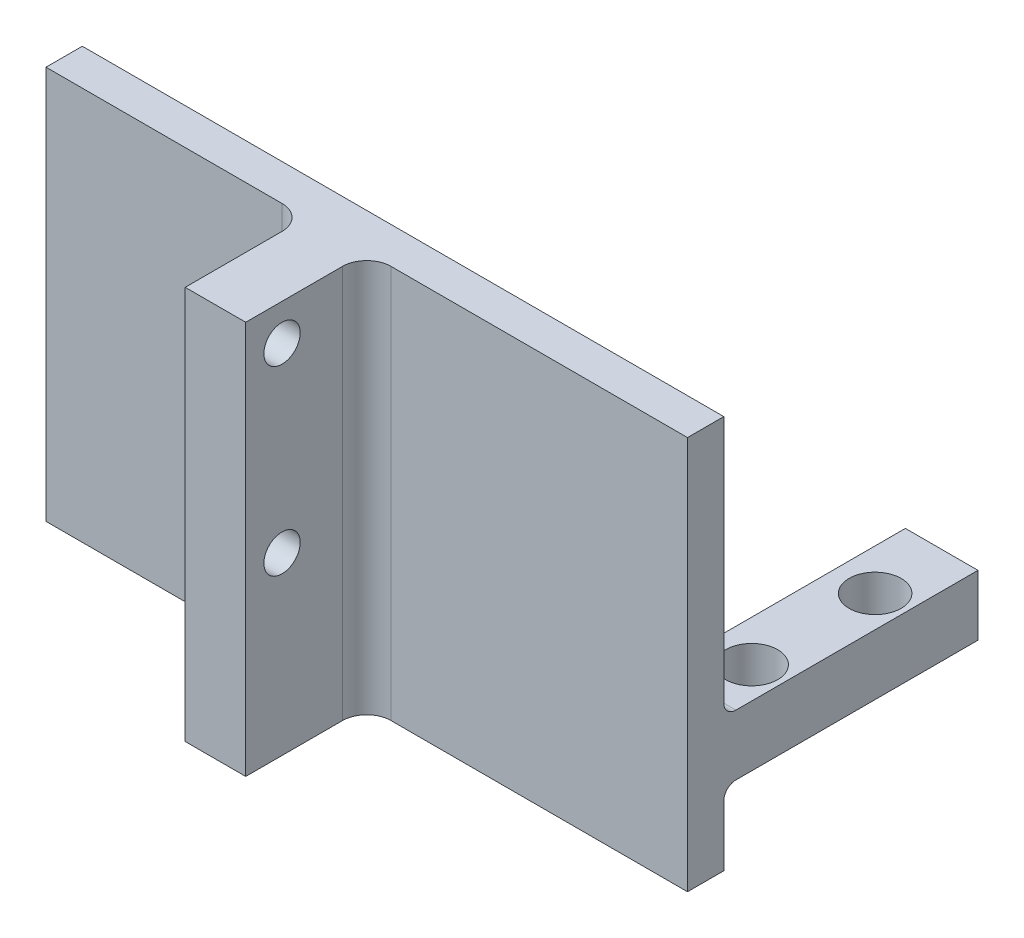
SolidWorks part; units mm, degrees
ref_plane "Front Plane" through (0, 0, 0) normal (0, 0, 1) x (1, 0, 0)
ref_plane "Top Plane" through (0, 0, 0) normal (0, 1, 0) x (1, 0, 0)
ref_plane "Right Plane" through (0, 0, 0) normal (1, 0, 0) x (0, 0, -1)
sketch "Sketch1" plane through (0, 0, 0) normal (0, 0, 1) x (1, 0, 0)
  line L0 (26.5, -7.5) -> (26.5, -5) construction
  line L1 (-26.5, 21.5) -> (26.5, 21.5)
  line L3 (-26.5, -11) -> (26.5, -11)
  line L4 (26.5, 21.5) -> (26.5, -11)
  line L8 (-26.5, 21.5) -> (-26.5, -11)
  line L9 (18, -11) -> (-18, -11) construction
  line L10 (-15.75, 21.5) -> (15.75, 21.5) construction
extrude "Boss-Extrude1" add sketch "Sketch1" along normal blind 3
sketch "Sketch2" plane through (0, 0, 0) normal (0, 0, -1) x (-1, 0, 0)
  line L0 (26.5, 0) -> (26.5, -5)
  line L1 (-20.5, -5) -> (-26.5, -5)
  line L2 (-26.5, -11) -> (-26.5, 21.5) construction
  line L3 (-20.5, -5) -> (-20.5, 0)
  line L4 (-20.5, 0) -> (-26.5, 0)
  line L5 (-26.5, 0) -> (-26.5, -5)
  line L6 (0, 21.5) -> (0, -11) construction
  line L7 (-26.5, 21.5) -> (26.5, 21.5) construction
  line L8 (26.5, -11) -> (-26.5, -11) construction
  line L9 (20.5, -5) -> (26.5, -5)
  line L10 (20.5, -5) -> (20.5, 0)
  line L11 (20.5, 0) -> (26.5, 0)
  dimension "D1" = 5
  dimension "D2" = 6
  dimension "D3" = 6
extrude "Boss-Extrude2" add sketch "Sketch2" along normal blind 21
fillet "Fillet1" radius 1 4 edges at (23.5, 0, 0) (-23.5, 0, 0) (-23.5, -5, 0) (23.5, -5, 0)
sketch "Sketch3" plane through (0, 0, 3) normal (0, 0, 1) x (1, 0, 0)
  line L1 (-5, 21.5) -> (-5, -11)
  line L2 (-5, 21.5) -> (0, 21.5)
  line L4 (0, 21.5) -> (0, -11)
  line L6 (0, -11) -> (-5, -11)
  line L8 (-26.5, 21.5) -> (-26.5, 1) construction
  line L9 (-26.5, -11) -> (26.5, -11) construction
  line L10 (26.5, 21.5) -> (-26.5, 21.5) construction
  dimension "D1" = 5
  dimension "D2" = 21.5
extrude "Boss-Extrude3" add sketch "Sketch3" along normal blind 10
fillet "Fillet2" radius 2 2 edges at (-5, 5.25, 3) (0, 5.25, 3)
sketch "Sketch4" plane through (0, -5, 0) normal (0, -1, 0) x (1, 0, 0)
  line L0 (-26.5, -21) -> (-26.5, -1) construction
  line L1 (-26.5, 0) -> (26.5, 0) construction
  line L2 (26.5, -21) -> (26.5, -1) construction
  circle A1 centre (23.9, -4.9) radius 2.15
  circle A2 centre (23.9, -15.1) radius 2.15
  circle A3 centre (-23.9, -4.9) radius 2.15
  circle A4 centre (-23.9, -15.1) radius 2.15
  dimension "D1" = 4.3
  dimension "D2" = 4.3
  dimension "D3" = 4.3
  dimension "D4" = 4.3
  dimension "D5" = 2.6
  dimension "D6" = 4.9
  dimension "D7" = 10.2
  dimension "D8" = 4.9
  dimension "D9" = 2.6
  dimension "D10" = 10.2
extrude "Cut-Extrude1" cut sketch "Sketch4" against normal blind 10
sketch "Sketch5" plane through (0, 0, 0) normal (1, 0, 0) x (0, 0, -1)
  line L1 (-13, 21.5) -> (-5, 21.5) construction
  line L2 (-13, -11) -> (-13, 21.5) construction
  circle A0 centre (-10, 18.5) radius 1.5
  circle A1 centre (-10, 3.5) radius 1.5
  dimension "D1" = 3
  dimension "D2" = 3
  dimension "D3" = 3
  dimension "D4" = 3
  dimension "D5" = 15
extrude "Cut-Extrude2" cut sketch "Sketch5" against normal blind 10
